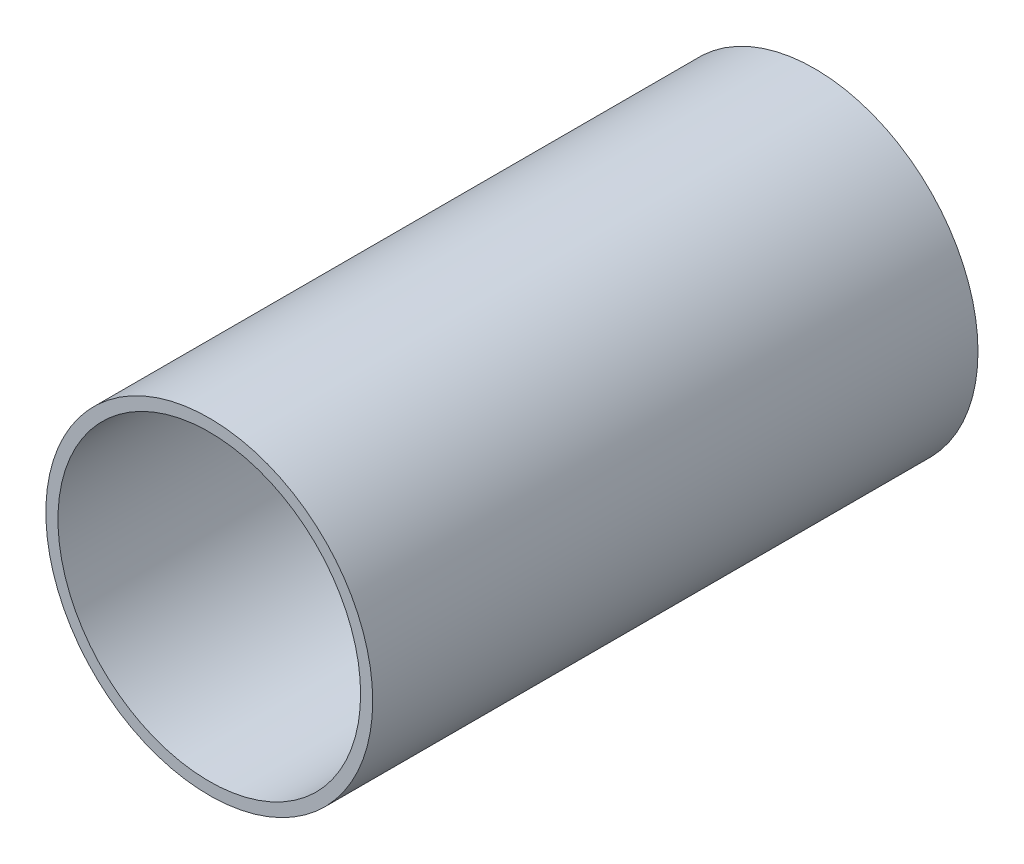
SolidWorks part; units mm, degrees
ref_plane "Front Plane" through (0, 0, 0) normal (0, 0, 1) x (1, 0, 0)
ref_plane "Top Plane" through (0, 0, 0) normal (0, 1, 0) x (1, 0, 0)
ref_plane "Right Plane" through (0, 0, 0) normal (1, 0, 0) x (0, 0, -1)
sketch "Sketch3" plane through (0, 0, 0) normal (0, 0, 1) x (1, 0, 0)
  circle A0 centre (0, 0) radius 13.5
  point P3 (0, 0)
  dimension "D1" = 27
extrude "Boss-Extrude1" add sketch "Sketch3" along normal blind 50
sketch "Sketch4" plane through (0, 0, 50) normal (0, 0, 1) x (1, 0, 0)
  circle A0 centre (0, 0) radius 12.5
  dimension "D1" = 25
extrude "Cut-Extrude1" cut sketch "Sketch4" against normal blind 100
